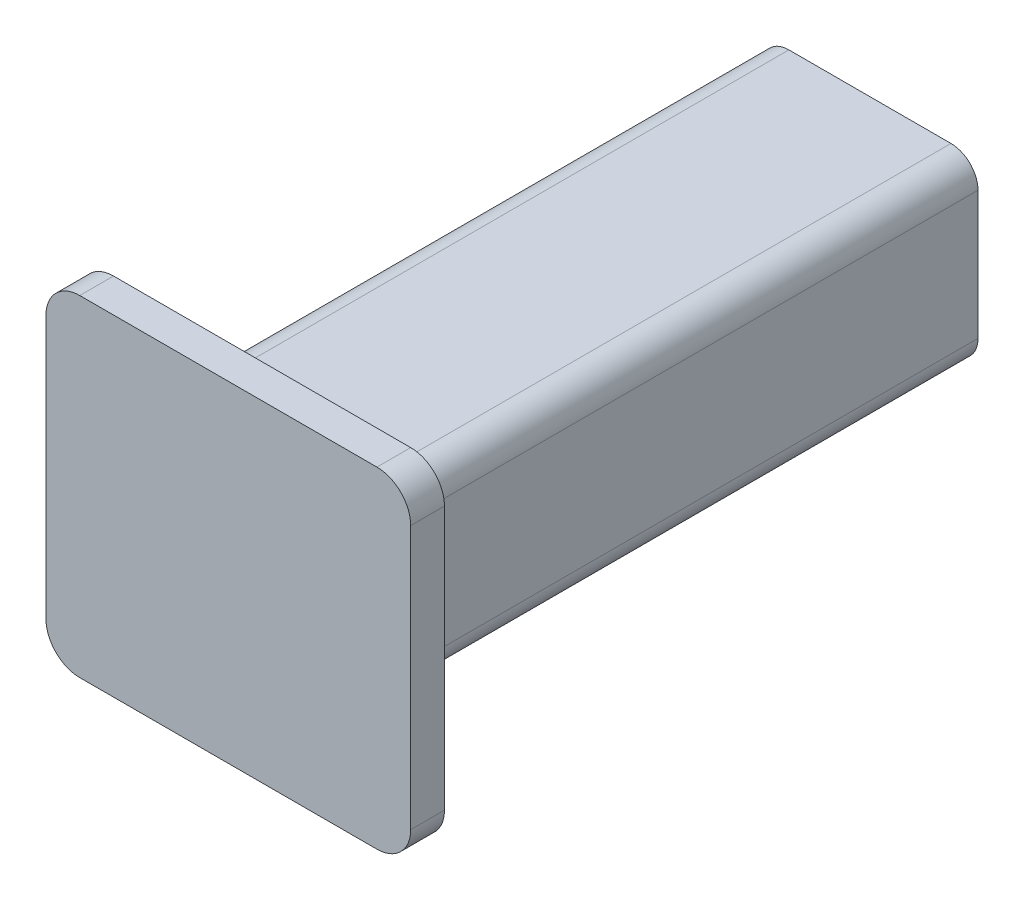
SolidWorks part; units mm, degrees
ref_plane "前视基准面" through (0, 0, 0) normal (0, 0, 1) x (1, 0, 0)
ref_plane "上视基准面" through (0, 0, 0) normal (0, 1, 0) x (1, 0, 0)
ref_plane "右视基准面" through (0, 0, 0) normal (1, 0, 0) x (0, 0, -1)
other "Configuration Table"
sketch "草图1" plane through (0, 0, 0) normal (0, 0, 1) x (1, 0, 0)
  line L1 (-3.1328, 7.3215) -> (5.6672, 7.3215)
  line L2 (-4.1328, 6.3215) -> (-4.1328, -1.4785)
  line L3 (-3.1328, -2.4785) -> (5.6672, -2.4785)
  line L4 (6.6672, 6.3215) -> (6.6672, -1.4785)
  arc A0 (5.6672, -2.4785) -> (6.6672, -1.4785) centre (5.6672, -1.4785) ccw
  arc A1 (-4.1328, -1.4785) -> (-3.1328, -2.4785) centre (-3.1328, -1.4785) ccw
  arc A2 (-3.1328, 7.3215) -> (-4.1328, 6.3215) centre (-3.1328, 6.3215) ccw
  arc A3 (5.6672, 7.3215) -> (6.6672, 6.3215) centre (5.6672, 6.3215) cw
  point P6 (6.6672, -2.4785)
  point P9 (-4.1328, -2.4785)
  point P12 (-4.1328, 7.3215)
  dimension "D3" = 1
  dimension "D1" = 10.8
  dimension "D2" = 9.8
extrude "凸台-拉伸1" add sketch "草图1" along normal blind 1
sketch "草图2" plane through (0, 0, 0) normal (0, 0, -1) x (-1, 0, 0)
  line L0 (-6.6672, -1.4785) -> (-6.6672, 6.3215) construction
  line L1 (-3.6672, 5.1215) -> (1.1328, 5.1215)
  line L2 (-4.4672, 4.3215) -> (-4.4672, 0.5215)
  line L3 (-3.6672, -0.2785) -> (1.1328, -0.2785)
  line L4 (1.9328, 4.3215) -> (1.9328, 0.5215)
  line L5 (4.1328, 6.3215) -> (4.1328, -1.4785) construction
  line L6 (-5.6672, 7.3215) -> (3.1328, 7.3215) construction
  line L7 (3.1328, -2.4785) -> (-5.6672, -2.4785) construction
  arc A0 (-4.4672, 0.5215) -> (-3.6672, -0.2785) centre (-3.6672, 0.5215) ccw
  arc A1 (1.1328, -0.2785) -> (1.9328, 0.5215) centre (1.1328, 0.5215) ccw
  arc A2 (1.1328, 5.1215) -> (1.9328, 4.3215) centre (1.1328, 4.3215) cw
  arc A3 (-3.6672, 5.1215) -> (-4.4672, 4.3215) centre (-3.6672, 4.3215) ccw
  dimension "D5" = 0.8
  dimension "D1" = 2.2
  dimension "D2" = 2.2
  dimension "D3" = 2.2
  dimension "D4" = 2.2
extrude "凸台-拉伸2" add sketch "草图2" along normal blind 18
